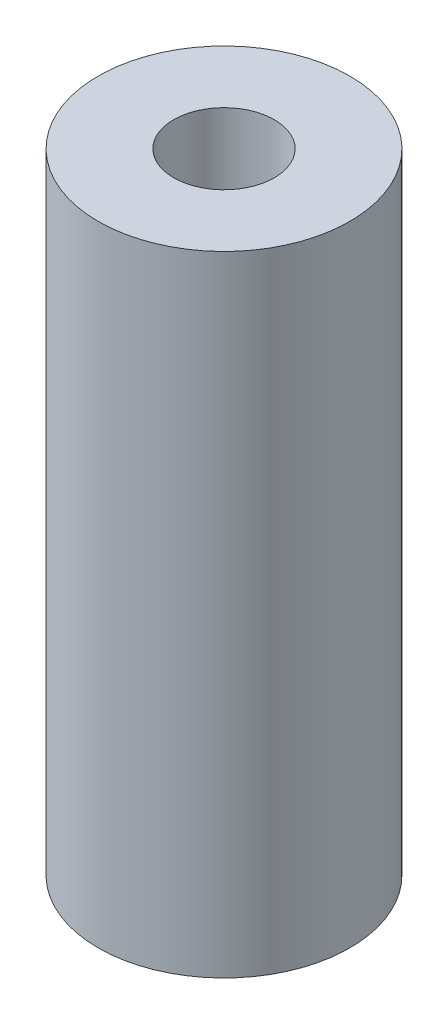
SolidWorks part; units mm, degrees
material "ABS"
ref_plane "前视基准面" through (0, 0, 0) normal (0, 0, 1) x (1, 0, 0)
ref_plane "上视基准面" through (0, 0, 0) normal (0, 1, 0) x (1, 0, 0)
ref_plane "右视基准面" through (0, 0, 0) normal (1, 0, 0) x (0, 0, -1)
sketch "草图1" plane through (0, 0, 0) normal (0, 1, 0) x (1, 0, 0)
  circle A0 centre (0, 0) radius 4
  circle A1 centre (0, 0) radius 1.6
  dimension "D1" = 8
  dimension "D2" = 3.2
extrude "凸台-拉伸1" add sketch "草图1" along normal blind 20
